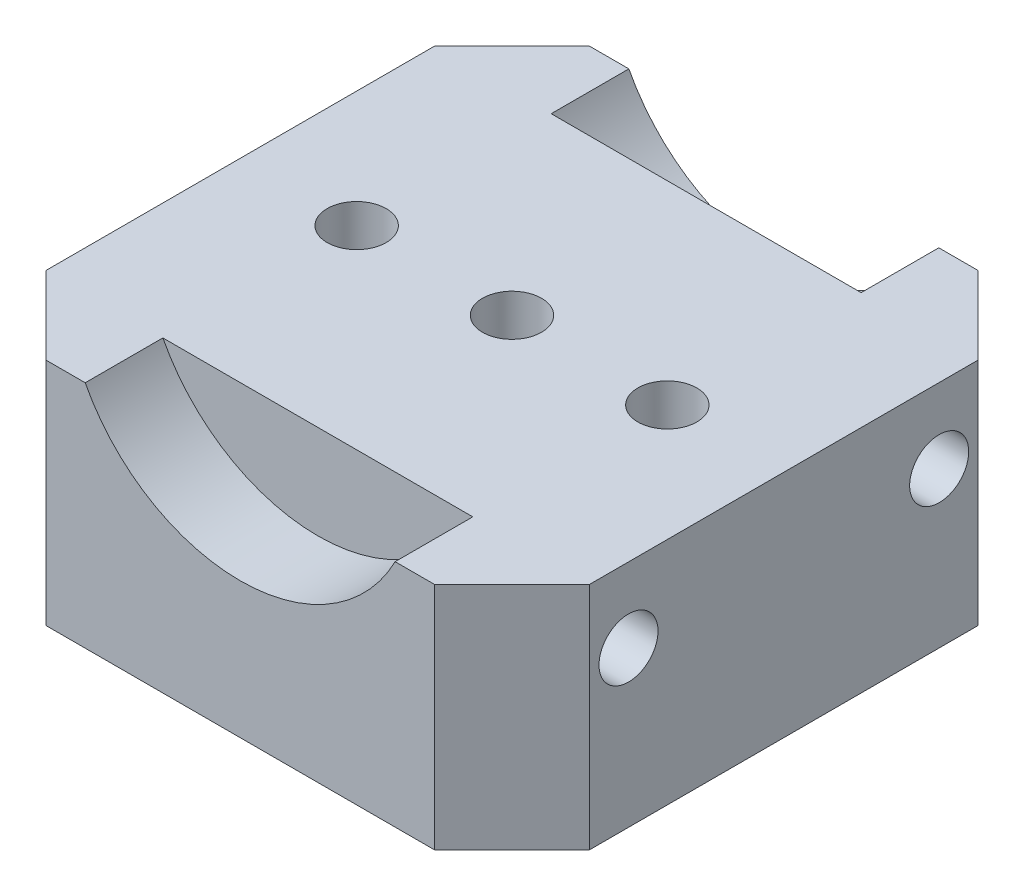
SolidWorks part; units mm, degrees
ref_plane "Front Plane" through (0, 0, 0) normal (0, 0, 1) x (1, 0, 0)
ref_plane "Top Plane" through (0, 0, 0) normal (0, 1, 0) x (1, 0, 0)
ref_plane "Right Plane" through (0, 0, 0) normal (1, 0, 0) x (0, 0, -1)
sketch "Sketch1" plane through (0, 0, 0) normal (0, 1, 0) x (1, 0, 0)
  line L0 (0, 38.1) -> (6.35, 44.45)
  line L1 (6.35, 0) -> (38.1, 0)
  line L2 (0, 6.35) -> (0, 38.1)
  line L3 (6.35, 44.45) -> (38.1, 44.45)
  line L4 (44.45, 6.35) -> (44.45, 38.1)
  line L5 (0, 6.35) -> (6.35, 0)
  line L6 (38.1, 0) -> (44.45, 6.35)
  line L7 (38.1, 44.45) -> (44.45, 38.1)
  line L9 (-3.175, 47.625) -> (47.625, 47.625) construction
  line L10 (-3.175, 47.625) -> (-3.175, -3.175) construction
  line L11 (-3.175, -3.175) -> (47.625, -3.175) construction
  line L12 (47.625, 47.625) -> (47.625, -3.175) construction
  circle A0 centre (9.525, 22.225) radius 2.413
  circle A1 centre (22.225, 22.225) radius 2.413
  circle A2 centre (34.925, 22.225) radius 2.413
  point P0 (0, 0)
  point P1 (44.45, 44.45)
  point P2 (0, 44.45)
  point P3 (44.45, 0)
  point P23 (47.625, 22.225)
  point P24 (0, 22.225)
  point P25 (22.225, 44.45)
  point P26 (22.225, 47.625)
  dimension "D3" = 4.826
  dimension "D1" = 44.45
  dimension "D2" = 44.45
  dimension "D4" = 50.8
  dimension "D5" = 25.4
  dimension "D6" = 12.7
  dimension "D7" = 12.7
extrude "Boss-Extrude1" add sketch "Sketch1" along normal blind 44.45
sketch "Sketch2" plane through (44.45, 0, 0) normal (1, 0, 0) x (0, 0, -1)
  line L0 (6.35, 0) -> (38.1, 0) construction
  line L1 (-3.175, 47.625) -> (47.625, 47.625) construction
  line L2 (-3.175, 47.625) -> (-3.175, -3.175) construction
  line L3 (-3.175, -3.175) -> (47.625, -3.175) construction
  line L4 (47.625, 47.625) -> (47.625, -3.175) construction
  line L5 (0, 44.45) -> (0, 0) construction
  line L6 (6.35, 44.45) -> (38.1, 44.45) construction
  circle A0 centre (9.525, 31.75) radius 2.413
  circle A1 centre (34.925, 31.75) radius 2.413
  circle A2 centre (34.925, 12.7) radius 2.413
  circle A3 centre (9.525, 12.7) radius 2.413
  point P11 (22.225, 0)
  point P16 (22.225, 47.625)
  point P19 (0, 22.225)
  point P20 (-3.175, 22.225)
  dimension "D1" = 4.826
  dimension "D2" = 50.8
  dimension "D3" = 12.7
  dimension "D4" = 12.7
  dimension "D5" = 12.7
  dimension "D6" = 19.05
extrude "Cut-Extrude1" cut sketch "Sketch2" against normal blind 50.8
sketch "Sketch3" plane through (44.45, 0, 0) normal (1, 0, 0) x (0, 0, -1)
  line L0 (44.45, 44.45) -> (44.45, 0) construction
  line L1 (0, 44.45) -> (44.45, 44.45)
  line L2 (0, 44.45) -> (0, 18.796)
  line L3 (0, 18.796) -> (44.45, 18.796)
  line L4 (44.45, 44.45) -> (44.45, 18.796)
  line L5 (6.35, 0) -> (38.1, 0) construction
  dimension "D1" = 18.796
extrude "Cut-Extrude2" cut sketch "Sketch3" against normal through all
sketch "Sketch4" plane through (0, 0, 0) normal (0, 0, 1) x (1, 0, 0)
  line L0 (22.225, 18.796) -> (22.225, -49981.204) construction
  line L1 (6.35, 18.796) -> (38.1, 18.796) construction
  line L2 (6.35, 0) -> (38.1, 0) construction
  circle A0 centre (22.225, 25.4) radius 14.2875
  point P6 (22.225, 18.796)
  point P7 (22.225, 15.7074)
  point P8 (22.225, 29.9599)
  dimension "D1" = 28.575
  dimension "D2" = 11.1125
extrude "Cut-Extrude3" cut sketch "Sketch4" against normal blind 6.35
ref_plane "Plane1" through (0, 0, -22.225) normal (0, 0, 1) x (1, 0, 0)
mirror "Mirror1" about plane through (0, 0, -22.225) normal (0, 0, 1) of "Cut-Extrude3"
